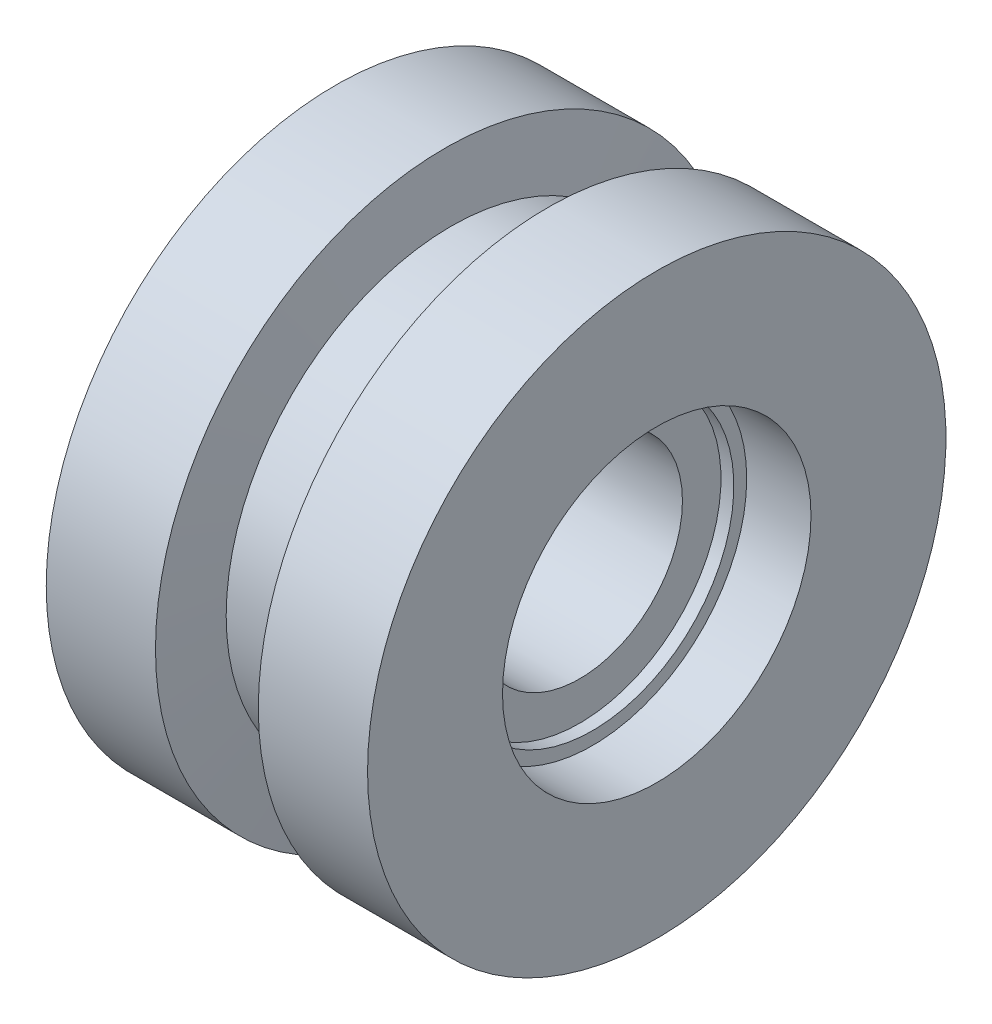
SolidWorks part; units mm, degrees
ref_plane "Front Plane" through (0, 0, 0) normal (0, 0, 1) x (1, 0, 0)
ref_plane "Top Plane" through (0, 0, 0) normal (0, 1, 0) x (1, 0, 0)
ref_plane "Right Plane" through (0, 0, 0) normal (1, 0, 0) x (0, 0, -1)
sketch "Sketch1" plane through (0, 0, 0) normal (0, 1, 0) x (1, 0, 0)
  line L0 (0, 0) -> (25, 0) construction
  line L2 (0, 22.5) -> (25, 22.5)
  line L3 (0, 22.5) -> (0, 12)
  line L5 (25, 22.5) -> (25, 12)
  line L16 (0, 12) -> (5, 12)
  line L21 (5, 12) -> (5, 10.997)
  line L22 (6, 8) -> (19, 8)
  line L23 (20, 10.997) -> (20, 12)
  line L24 (20, 12) -> (25, 12)
  line L25 (5, 10.997) -> (6, 10.997)
  line L26 (6, 10.997) -> (6, 8)
  line L27 (20, 10.997) -> (19, 10.997)
  line L28 (19, 10.997) -> (19, 8)
  dimension "D2" = 45
  dimension "D3" = 25
  dimension "D1" = 24
  dimension "D4" = 16
  dimension "D5" = 5
  dimension "D6" = 5
  dimension "D7" = 1
  dimension "D8" = 1.003
  dimension "D9" = 1
revolve "Revolve1" add sketch "Sketch1" angle 360 about L0
sketch "Sketch4" plane through (0, 0, 0) normal (0, 1, 0) x (1, 0, 0)
  line L0 (8.5, 22.5) -> (9, 17.5)
  line L1 (25, 22.5) -> (0, 22.5) construction
  line L2 (9, 17.5) -> (16, 17.5)
  line L3 (16, 17.5) -> (16.5, 22.5)
  line L4 (25, 22.5) -> (0, 22.5) construction
  line L5 (16.5, 22.5) -> (8.5, 22.5)
  line L6 (12.5, 22.5) -> (12.5, 17.5) construction
  line L7 (25, 22.5) -> (0, 22.5) construction
  line L8 (0, 0) -> (25, 0) construction
  line L9 (0, 22.5) -> (0, -22.5) construction
  line L11 (25, -22.5) -> (25, 22.5) construction
  point P10 (12.5, 0)
  point P11 (21.7135, 0)
  dimension "D1" = 8
  dimension "D2" = 5
  dimension "D3" = 7
revolve "Cut-Revolve1" cut sketch "Sketch4" angle 360 about L8
move or copy body "Body-Move/Copy1" [suppressed] bodies to move or copy 102
equation "\"D9@Sketch1\"=\"D7@Sketch1\""
